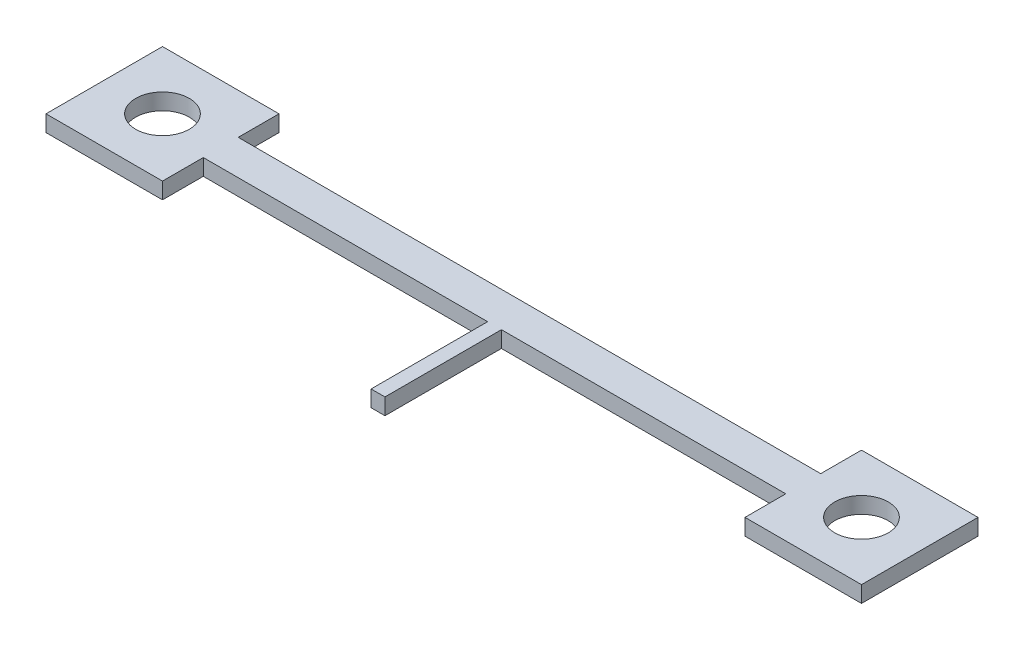
SolidWorks part; units mm, degrees
material "Commercially Pure CP-Ti UNS R50400 (SS)"
ref_plane "Front Plane" through (0, 0, 0) normal (0, 0, 1) x (1, 0, 0)
ref_plane "Top Plane" through (0, 0, 0) normal (0, 1, 0) x (1, 0, 0)
ref_plane "Right Plane" through (0, 0, 0) normal (1, 0, 0) x (0, 0, -1)
sketch "Sketch1" plane through (0, 0, 0) normal (0, 1, 0) x (1, 0, 0)
  line L0 (-41.424, -10.2833) -> (-41.424, -12.5058)
  line L1 (-47.774, -12.5058) -> (-41.424, -12.5058)
  line L2 (-47.774, -12.5058) -> (-47.774, -6.1558)
  line L3 (-47.774, -6.1558) -> (-41.424, -6.1558)
  line L4 (-3.324, -12.5058) -> (-3.324, -6.1558)
  line L7 (-41.424, -10.2833) -> (-9.674, -10.2833)
  line L9 (-41.424, -8.3783) -> (-9.674, -8.3783)
  line L13 (-41.424, -8.3783) -> (-41.424, -6.1558)
  line L14 (-9.674, -8.3783) -> (-9.674, -6.1558)
  line L15 (-9.674, -10.2833) -> (-9.674, -12.5058)
  line L16 (-9.674, -6.1558) -> (-3.324, -6.1558)
  line L17 (-9.674, -12.5058) -> (-3.324, -12.5058)
  point P0 (0, 0)
  point P6 (0, 0)
  dimension "D1" = 44.45
  dimension "D2" = 6.35
  dimension "D3" = 6.35
  dimension "D4" = 1.905
extrude "Boss-Extrude1" add sketch "Sketch1" along normal mid plane 0.889
hole_wizard "#97 (0.0059) Diameter Hole1" positions "Sketch4" profile "Sketch3" hole size "#97" standard "Ansi Inch" end condition through all
sketch "Sketch4" plane through (0, 0.4445, 0) normal (0, 1, 0) x (-1, 0, 0)
  line L0 (47.774, 12.5058) -> (41.424, 6.1558) construction
  point P0 (44.599, 9.3308)
sketch "Sketch3" plane through (-44.599, 0.4445, 9.3308) normal (1, 0, 0) x (0, 0, 1)
  line L0 (0, 0) -> (0, 0.889)
  line L1 (0, 0.889) -> (1.4605, 0.889)
  line L2 (1.4605, 0.889) -> (1.4605, 0)
  line L5 (1.4605, 0) -> (0, 0)
  line L11 (0, -6.35) -> (0, 107.95) construction
  dimension "Thru Hole Dia." = 2.921
  dimension "Thru Hole Depth" = 0.889
ref_plane "Plane1" through (-25.549, 0, 0) normal (1, 0, 0) x (0, 0, -1)
mirror "Mirror1" about plane through (-25.549, 0, 0) normal (1, 0, 0) of "#97 (0.0059) Diameter Hole1"
sketch "Sketch7" plane through (0, 0, 10.2833) normal (0, 0, 1) x (1, 0, 0)
  line L1 (-41.424, 0.4445) -> (-9.674, 0.4445) construction
  line L3 (-25.799, 0.4445) -> (-25.299, 0.4445)
  line L4 (-25.299, -0.4445) -> (-25.799, -0.4445)
  line L5 (-41.424, -0.4445) -> (-9.674, -0.4445) construction
  line L6 (-25.799, -0.4445) -> (-25.799, 0.4445)
  line L7 (-25.299, 0.4445) -> (-25.299, -0.4445)
extrude "Boss-Extrude2" add sketch "Sketch7" along normal blind 6.35
sketch "Sketch11" plane through (-25.799, 0, 0) normal (-1, 0, 0) x (0, 0, 1)
  line L1 (10.2833, 0.4445) -> (16.6333, 0.4445)
  line L2 (10.2833, 0.4445) -> (10.2833, -0.4445)
  line L3 (10.2833, -0.4445) -> (16.6333, -0.4445)
  line L4 (16.6333, 0.4445) -> (16.6333, -0.4445)
extrude "Boss-Extrude3" add sketch "Sketch11" along normal blind 0.127
sketch "Sketch12" plane through (-25.299, 0, 0) normal (1, 0, 0) x (0, 0, -1)
  line L1 (-10.2833, 0.4445) -> (-16.6333, 0.4445)
  line L2 (-10.2833, 0.4445) -> (-10.2833, -0.4445)
  line L3 (-10.2833, -0.4445) -> (-16.6333, -0.4445)
  line L4 (-16.6333, 0.4445) -> (-16.6333, -0.4445)
extrude "Boss-Extrude4" add sketch "Sketch12" along normal blind 0.127
